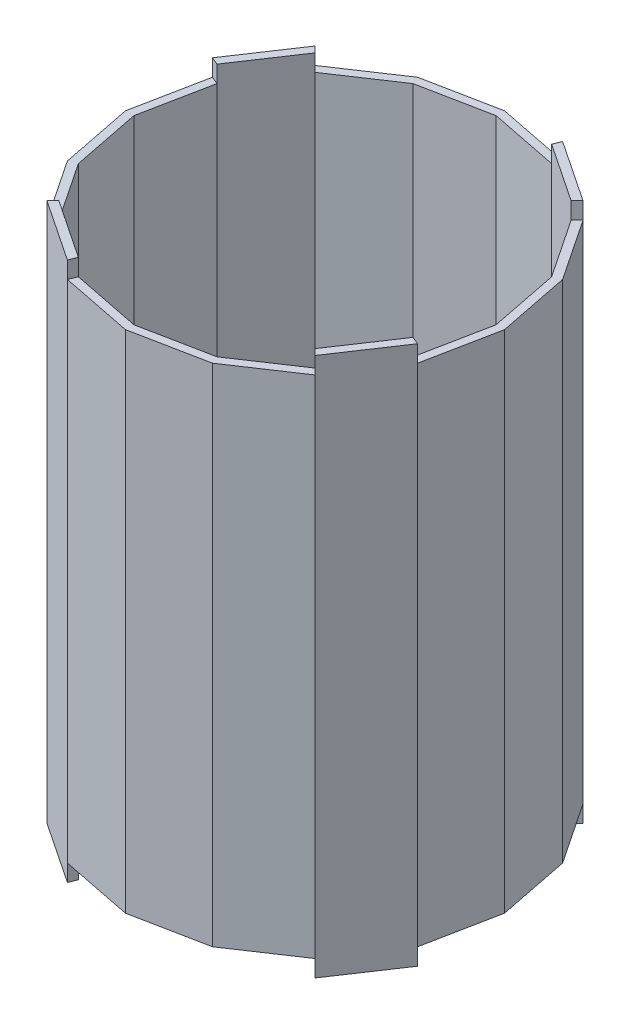
SolidWorks part; units mm, degrees
ref_plane "Front Plane" through (0, 0, 0) normal (0, 0, 1) x (1, 0, 0)
ref_plane "Top Plane" through (0, 0, 0) normal (0, 1, 0) x (1, 0, 0)
ref_plane "Right Plane" through (0, 0, 0) normal (1, 0, 0) x (0, 0, -1)
sketch "Sketch1" plane through (0, 0, 0) normal (0, 1, 0) x (1, 0, 0)
  line L0 (-40.4112, -40.4112) -> (-21.8704, -52.7997)
  line L1 (0, 57.15) -> (-21.8704, 52.7997)
  line L2 (-21.8704, 52.7997) -> (-40.4112, 40.4112)
  line L3 (-40.4112, 40.4112) -> (-52.7997, 21.8704)
  line L4 (-52.7997, 21.8704) -> (-57.15, 0)
  line L5 (-57.15, 0) -> (-52.7997, -21.8704)
  line L6 (-52.7997, -21.8704) -> (-40.4112, -40.4112)
  line L7 (-21.8704, -52.7997) -> (0, -57.15)
  line L8 (0, -57.15) -> (21.8704, -52.7997)
  line L9 (21.8704, -52.7997) -> (40.4112, -40.4112)
  line L10 (40.4112, -40.4112) -> (52.7997, -21.8704)
  line L11 (52.7997, -21.8704) -> (57.15, 0)
  line L12 (57.15, 0) -> (52.7997, 21.8704)
  line L13 (52.7997, 21.8704) -> (40.4112, 40.4112)
  line L14 (40.4112, 40.4112) -> (21.8704, 52.7997)
  line L15 (21.8704, 52.7997) -> (0, 57.15)
  line L17 (0, 54.61) -> (-20.8983, 50.4531)
  line L18 (-20.8983, 50.4531) -> (-38.6151, 38.6151)
  line L19 (-38.6151, 38.6151) -> (-50.4531, 20.8983)
  line L20 (-50.4531, 20.8983) -> (-54.61, 0)
  line L21 (-54.61, 0) -> (-50.4531, -20.8983)
  line L22 (-50.4531, -20.8983) -> (-38.6151, -38.6151)
  line L23 (-38.6151, -38.6151) -> (-20.8983, -50.4531)
  line L24 (-20.8983, -50.4531) -> (0, -54.61)
  line L25 (0, -54.61) -> (20.8983, -50.4531)
  line L26 (20.8983, -50.4531) -> (38.6151, -38.6151)
  line L27 (38.6151, -38.6151) -> (50.4531, -20.8983)
  line L28 (50.4531, -20.8983) -> (54.61, 0)
  line L29 (54.61, 0) -> (50.4531, 20.8983)
  line L30 (50.4531, 20.8983) -> (38.6151, 38.6151)
  line L31 (38.6151, 38.6151) -> (20.8983, 50.4531)
  line L32 (20.8983, 50.4531) -> (0, 54.61)
  circle A0 centre (0, 0) radius 56.0519 construction
  circle A1 centre (0, 0) radius 53.5607 construction
  dimension "D1" = 114.3
  dimension "D2" = 2.54
extrude "Boss-Extrude1" add sketch "Sketch1" along normal blind 152.4
sketch "Sketch2" plane through (0, 152.4, 0) normal (0, 1, 0) x (1, 0, 0)
  line L0 (-52.7997, 21.8704) -> (-50.4531, 20.8983)
  line L1 (-50.4531, 20.8983) -> (-38.6151, 38.6151)
  line L2 (-38.6151, 38.6151) -> (-40.4112, 40.4112)
  line L3 (-40.4112, 40.4112) -> (-52.7997, 21.8704)
  line L4 (-38.6151, -38.6151) -> (-20.8983, -50.4531)
  line L5 (-20.8983, -50.4531) -> (-21.8704, -52.7997)
  line L6 (-21.8704, -52.7997) -> (-40.4112, -40.4112)
  line L7 (-40.4112, -40.4112) -> (-38.6151, -38.6151)
  line L8 (38.6151, -38.6151) -> (40.4112, -40.4112)
  line L9 (40.4112, -40.4112) -> (52.7997, -21.8704)
  line L10 (52.7997, -21.8704) -> (50.4531, -20.8983)
  line L11 (50.4531, -20.8983) -> (38.6151, -38.6151)
  line L12 (40.4112, 40.4112) -> (38.6151, 38.6151)
  line L13 (38.6151, 38.6151) -> (20.8983, 50.4531)
  line L14 (20.8983, 50.4531) -> (21.8704, 52.7997)
  line L15 (21.8704, 52.7997) -> (40.4112, 40.4112)
extrude "Boss-Extrude2" add sketch "Sketch2" along normal blind 5.08
sketch "Sketch3" plane through (0, 0, 0) normal (0, -1, 0) x (1, 0, 0)
  line L0 (38.6151, -38.6151) -> (40.4112, -40.4112)
  line L1 (40.4112, -40.4112) -> (21.8704, -52.7997)
  line L2 (21.8704, -52.7997) -> (20.8983, -50.4531)
  line L3 (20.8983, -50.4531) -> (38.6151, -38.6151)
  line L4 (50.4531, 20.8983) -> (52.7997, 21.8704)
  line L5 (52.7997, 21.8704) -> (40.4112, 40.4112)
  line L6 (40.4112, 40.4112) -> (38.6151, 38.6151)
  line L7 (38.6151, 38.6151) -> (50.4531, 20.8983)
  line L8 (-40.4112, 40.4112) -> (-38.6151, 38.6151)
  line L11 (-38.6151, 38.6151) -> (-20.8983, 50.4531)
  line L12 (-20.8983, 50.4531) -> (-21.8704, 52.7997)
  line L13 (-21.8704, 52.7997) -> (-40.4112, 40.4112)
  line L14 (-50.4531, -20.8983) -> (-38.6151, -38.6151)
  line L15 (-38.6151, -38.6151) -> (-40.4112, -40.4112)
  line L16 (-40.4112, -40.4112) -> (-52.7997, -21.8704)
  line L17 (-52.7997, -21.8704) -> (-50.4531, -20.8983)
extrude "Boss-Extrude3" add sketch "Sketch3" along normal blind 5.08
equation "\"MDF\"= .2"
equation "\"Foamcore\"= .1"
equation "\"GMaterial\"= \"MDF\""
equation "\"CutDistance\" = .1"
equation "\"D2@Sketch1\"=\"Foamcore\""
equation "\"D1@Boss-Extrude2\"=\"GMaterial\""
equation "\"D1@Boss-Extrude3\"=\"GMaterial\""
